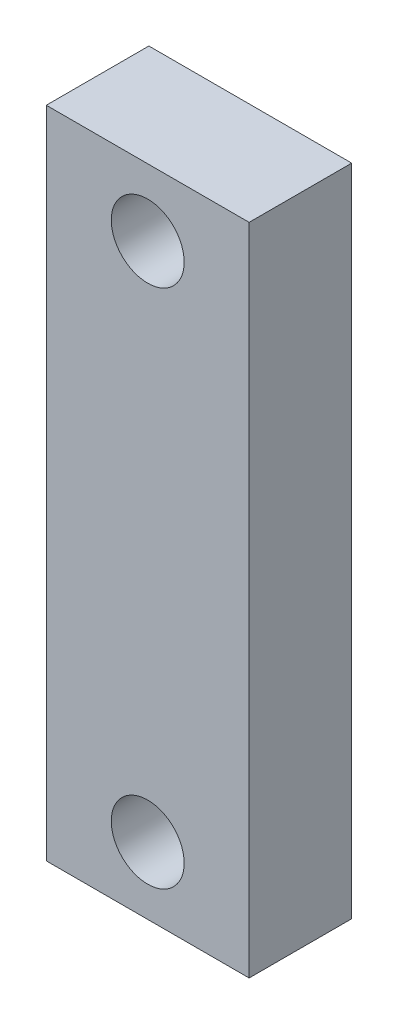
SolidWorks part; units mm, degrees
ref_plane "Alzado" through (0, 0, 0) normal (0, 0, 1) x (1, 0, 0)
ref_plane "Planta" through (0, 0, 0) normal (0, 1, 0) x (1, 0, 0)
ref_plane "Vista lateral" through (0, 0, 0) normal (1, 0, 0) x (0, 0, -1)
sketch "Sketch1" plane through (0, 0, 0) normal (0, 0, 1) x (1, 0, 0)
  line L1 (0, 0) -> (26.5, 0)
  line L2 (0, 0) -> (0, 85.5)
  line L3 (0, 85.5) -> (26.5, 85.5)
  line L4 (26.5, 0) -> (26.5, 85.5)
  dimension "D1" = 85.5
  dimension "D2" = 26.5
extrude "Boss-Extrude1" add sketch "Sketch1" along normal blind 13.4
sketch "Sketch2" plane through (0, 0, 13.4) normal (0, 0, 1) x (1, 0, 0)
  line L0 (0, 42.75) -> (26.5, 42.75)
  line L1 (13.25, 42.75) -> (13.25, 76.75) construction
  line L2 (13.25, 42.75) -> (13.25, 8.75) construction
  line L4 (0, 85.5) -> (0, 0)
  line L5 (0, 0) -> (26.5, 0)
  line L6 (26.5, 0) -> (26.5, 85.5)
  line L7 (26.5, 85.5) -> (0, 85.5)
  line L8 (0, 85.5) -> (0, 0) construction
  line L9 (0, 0) -> (26.5, 0) construction
  line L10 (26.5, 0) -> (26.5, 85.5) construction
  line L11 (26.5, 85.5) -> (0, 85.5) construction
  circle A0 centre (13.25, 76.75) radius 4.7625
  circle A1 centre (13.25, 8.75) radius 4.7625
  dimension "D4" = 9.525
  dimension "D5" = 9.525
  dimension "D2" = 34
  dimension "D3" = 34
  dimension "D1" = 0
extrude "Cut-Extrude1" cut sketch "Sketch2" against normal up to surface (13.4 mm away) contours A1 | A0 up to face at (13.25, 42.75, 0)
